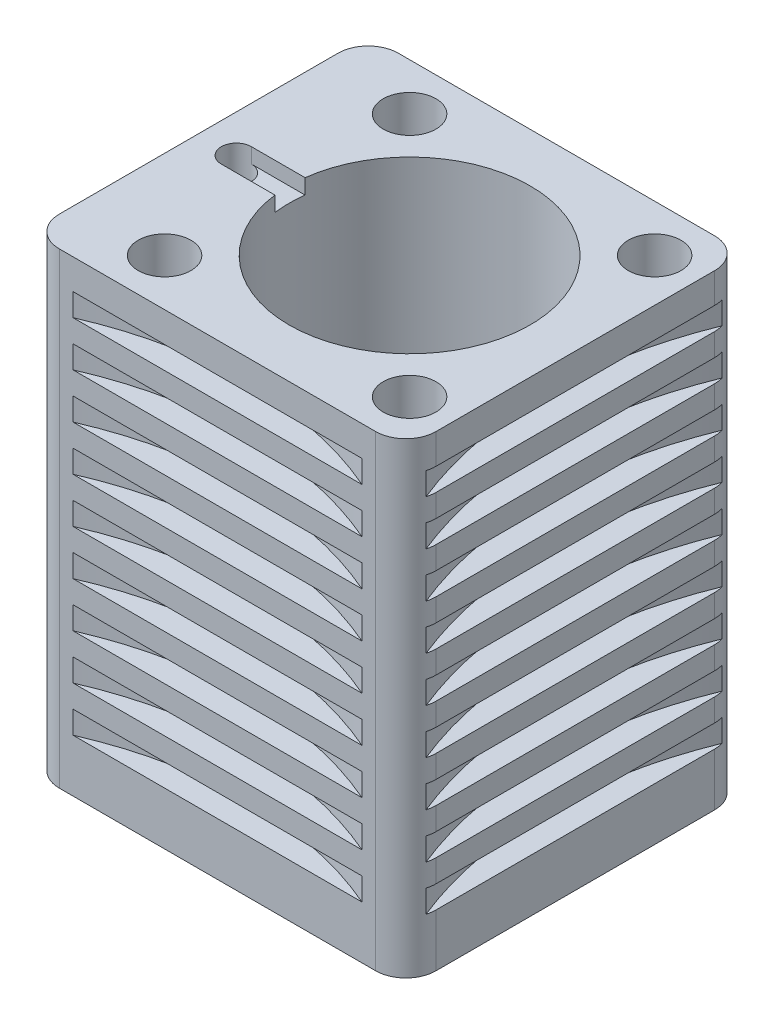
SolidWorks part; units mm, degrees
ref_plane "Front Plane" through (0, 0, 0) normal (0, 0, 1) x (1, 0, 0)
ref_plane "Top Plane" through (0, 0, 0) normal (0, 1, 0) x (1, 0, 0)
ref_plane "Right Plane" through (0, 0, 0) normal (1, 0, 0) x (0, 0, -1)
sketch "Sketch1" plane through (0, 0, 0) normal (0, 1, 0) x (1, 0, 0)
  line L5 (18, 22.5) -> (-24, 22.5)
  line L6 (22, 18.5) -> (22, -18.5)
  line L7 (18, -22.5) -> (-24, -22.5)
  line L8 (-28, 18.5) -> (-28, -18.5)
  arc A0 (18, -22.5) -> (22, -18.5) centre (18, -18.5) ccw
  arc A1 (-24, -22.5) -> (-28, -18.5) centre (-24, -18.5) cw
  arc A2 (22, 18.5) -> (18, 22.5) centre (18, 18.5) ccw
  arc A3 (-24, 22.5) -> (-28, 18.5) centre (-24, 18.5) ccw
  point P8 (22, -22.5)
  point P11 (-28, -22.5)
  point P16 (-28, 22.5)
  dimension "D5" = 4
  dimension "D1" = 45
  dimension "D2" = 50
  dimension "D3" = 22
  dimension "D4" = 22.5
extrude "Boss-Extrude1" add sketch "Sketch1" against normal blind 62
sketch "Sketch3" plane through (0, -62, 0) normal (0, -1, 0) x (1, 0, 0)
  circle A0 centre (0, 0) radius 18
  dimension "D1" = 36
extrude "Boss-Extrude2" add sketch "Sketch3" along normal blind 2
sketch "Sketch4" plane through (0, 0, 0) normal (0, 1, 0) x (1, 0, 0)
  circle A0 centre (0, 0) radius 16
  dimension "D1" = 32
extrude "Cut-Extrude1" cut sketch "Sketch4" against normal through all
sketch "Sketch5" plane through (0, 0, 0) normal (0, 1, 0) x (1, 0, 0)
  line L0 (-23, 0) -> (-11, 0) construction
  line L1 (-23, 2) -> (-11, 2)
  line L2 (-23, -2) -> (-11, -2)
  circle A0 centre (0, 0) radius 23 construction
  arc A1 (-23, 2) -> (-23, -2) centre (-23, 0) ccw
  arc A2 (-11, -2) -> (-11, 2) centre (-11, 0) ccw
  point P5 (-17, 0)
  dimension "D1" = 46
  dimension "D2" = 2
  dimension "D3" = 12
extrude "Cut-Extrude2" cut sketch "Sketch5" against normal blind 2
sketch "Sketch6" plane through (0, -2, 0) normal (0, 1, 0) x (1, 0, 0)
  circle A0 centre (-23, 0) radius 2
extrude "Cut-Extrude3" cut sketch "Sketch6" against normal through all
sketch "Sketch7" plane through (0, 0, 0) normal (0, 1, 0) x (1, 0, 0)
  line L0 (0, 0) -> (60.2064, 0) construction
  line L1 (0, 0) -> (0, 41.4038) construction
  line L2 (0, 0) -> (16.2635, 16.2635) construction
  circle A0 centre (0, 0) radius 23 construction
  circle A1 centre (16.2635, 16.2635) radius 3.5
  circle A2 centre (16.2635, -16.2635) radius 3.5
  circle A3 centre (-16.2635, -16.2635) radius 3.5
  circle A4 centre (-16.2635, 16.2635) radius 3.5
  point P16 (0, 0)
  dimension "D1" = 46
  dimension "D2" = 7
  dimension "D3" = 45
  dimension "D4" = 4
extrude "Cut-Extrude4" cut sketch "Sketch7" against normal through all
ref_plane "Plane1" through (-3, 0, 0) normal (1, 0, 0) x (0, 0, -1)
sketch "Sketch8" plane through (-3, 0, 0) normal (1, 0, 0) x (0, 0, -1)
  line L0 (-22.5, -62) -> (-22.5, 0) construction
  line L1 (-18.5, -4) -> (-66.5, -4)
  line L2 (-18.5, -4) -> (-18.5, -7)
  line L3 (-18.5, -7) -> (-66.5, -7)
  line L4 (-66.5, -4) -> (-66.5, -7)
  line L5 (-18.5, 0) -> (-22.5, 0) construction
  dimension "D1" = 4
  dimension "D2" = 4
  dimension "D3" = 48
  dimension "D4" = 3
revolve "Cut-Revolve1" cut sketch "Sketch8" angle 360 about L4
pattern_linear "LPattern1" count 9 spacing 6 along (0, -1, 0) of "Cut-Revolve1"
mirror "Mirror1" about plane through (0, 0, 0) normal (0, 0, 1) of "LPattern1", "Cut-Revolve1"
sketch "Sketch11" plane through (0, 0, 0) normal (0, 0, 1) x (1, 0, 0)
  line L0 (-22.1833, -4) -> (16.1833, -4) construction
  line L1 (18, -4) -> (70.2651, -4)
  line L2 (18, -4) -> (18, -7)
  line L3 (18, -7) -> (70.2651, -7)
  line L4 (70.2651, -4) -> (70.2651, -7)
  line L5 (-24, 0) -> (18, 0) construction
  line L6 (22, -62) -> (22, 0) construction
  dimension "D1" = 3
  dimension "D2" = 4
  dimension "D3" = 4
revolve "Cut-Revolve3" cut sketch "Sketch11" angle 360 about L4
pattern_linear "LPattern2" count 9 spacing 6 along (0, -1, 0) of "Cut-Revolve3"
